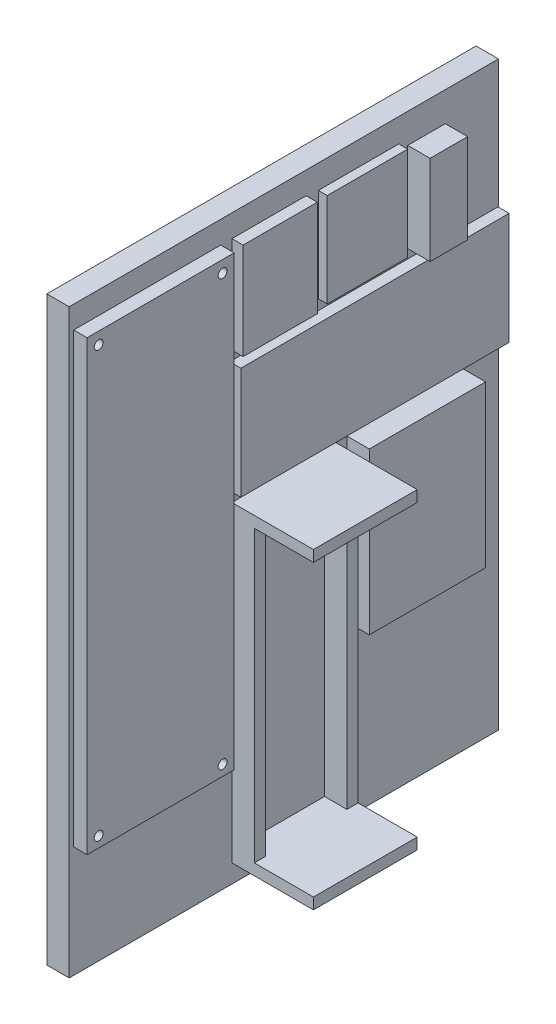
SolidWorks part; units mm, degrees
material "1060 Alloy"
ref_plane "Front Plane" through (0, 0, 0) normal (0, 0, 1) x (1, 0, 0)
ref_plane "Top Plane" through (0, 0, 0) normal (0, 1, 0) x (1, 0, 0)
ref_plane "Right Plane" through (0, 0, 0) normal (1, 0, 0) x (0, 0, -1)
sketch "Sketch1" plane through (0, 0, 0) normal (1, 0, 0) x (0, 0, -1)
  line L1 (-16.445, 50.065) -> (16.445, 50.065)
  line L2 (-16.445, 50.065) -> (-16.445, -50.065)
  line L3 (-16.445, -50.065) -> (16.445, -50.065)
  line L4 (16.445, 50.065) -> (16.445, -50.065)
  line L5 (-17.445, 55.065) -> (78.555, 55.065)
  line L6 (-17.445, 55.065) -> (-17.445, -74.935)
  line L7 (-17.445, -74.935) -> (78.555, -74.935)
  line L8 (78.555, 55.065) -> (78.555, -74.935)
  circle A0 centre (-13.855, 47.395) radius 1
  circle A4 centre (13.855, 47.395) radius 1
  circle A5 centre (13.855, -47.705) radius 1
  circle A6 centre (-13.855, -47.705) radius 1
  dimension "D3" = 2
  dimension "D4" = 2.67
  dimension "D8" = 2
  dimension "D11" = 2
  dimension "D12" = 2
  dimension "D15" = 2.36
  dimension "D1" = 32.89
  dimension "D2" = 100.13
  dimension "D5" = 2.59
  dimension "D6" = 50.065
  dimension "D7" = 16.445
  dimension "D9" = 2.59
  dimension "D10" = 2.67
  dimension "D13" = 2.59
  dimension "D14" = 2.36
  dimension "D16" = 2.59
  dimension "D17" = 95.1
  dimension "D18" = 130
  dimension "D19" = 96
  dimension "D20" = 5
  dimension "D21" = 1
extrude "Boss-Extrude1" add sketch "Sketch1" along normal blind 5 contours L4 L1 L2 L3 A6 A5 A4 A0 | L8 L5 L6 L7 L1 L4 L3 L2
sketch "Sketch3" plane through (5, 0, 0) normal (1, 0, 0) x (0, 0, -1)
  line L1 (-16.445, 50.065) -> (16.445, 50.065)
  line L2 (-16.445, 50.065) -> (-16.445, -50.065)
  line L3 (-16.445, -50.065) -> (16.445, -50.065)
  line L4 (16.445, 50.065) -> (16.445, -50.065)
  circle A0 centre (-13.855, 47.395) radius 1 construction
  circle A1 centre (13.855, 47.395) radius 1 construction
  circle A2 centre (13.855, -47.705) radius 1 construction
  circle A3 centre (-13.855, 47.395) radius 1
  circle A4 centre (13.855, 47.395) radius 1
  circle A5 centre (13.855, -47.705) radius 1
  circle A6 centre (-13.855, -47.705) radius 1
  dimension "D5" = 2
  dimension "D6" = 2.36
  dimension "D1" = 2.59
  dimension "D2" = 2.59
  dimension "D3" = 2.67
  dimension "D4" = 2.36
  dimension "D7" = 2.59
extrude "Boss-Extrude3" add sketch "Sketch3" along normal blind 3
sketch "Sketch4" plane through (5, 0, 0) normal (1, 0, 0) x (0, 0, -1)
  line L1 (18.945, 50.065) -> (35.545, 50.065)
  line L2 (18.945, 50.065) -> (18.945, 28.465)
  line L3 (18.945, 28.465) -> (35.545, 28.465)
  line L4 (35.545, 50.065) -> (35.545, 28.465)
  line L10 (16.445, -50.065) -> (16.445, 50.065) construction
  line L11 (16.445, 50.065) -> (-16.445, 50.065) construction
  point P4 (35.545, 39.265)
  point P7 (0, 50.065)
  dimension "D1" = 16.6
  dimension "D2" = 21.6
  dimension "D3" = 0
  dimension "D6" = 2.5
extrude "Boss-Extrude4" add sketch "Sketch4" along normal blind 2.5
sketch "Sketch5" plane through (5, 0, 0) normal (1, 0, 0) x (0, 0, -1)
  line L1 (18.445, 26.465) -> (78.445, 26.465)
  line L2 (18.445, 26.465) -> (18.445, 1.465)
  line L3 (18.445, 1.465) -> (78.445, 1.465)
  line L4 (78.445, 26.465) -> (78.445, 1.465)
  line L5 (18.945, 28.465) -> (35.545, 28.465) construction
  line L6 (16.445, -50.065) -> (16.445, 50.065) construction
  dimension "D1" = 60
  dimension "D2" = 25
  dimension "D3" = 2
  dimension "D4" = 2
extrude "Boss-Extrude5" add sketch "Sketch5" along normal blind 2.5
sketch "Sketch6" plane through (5, 0, 0) normal (1, 0, 0) x (0, 0, -1)
  line L1 (38.2605, 49.7462) -> (56.2605, 49.7462)
  line L2 (38.2605, 49.7462) -> (38.2605, 28.7462)
  line L3 (38.2605, 28.7462) -> (56.2605, 28.7462)
  line L4 (56.2605, 49.7462) -> (56.2605, 28.7462)
  dimension "D1" = 18
  dimension "D2" = 21
extrude "Boss-Extrude6" add sketch "Sketch6" along normal blind 2
sketch "Sketch7" plane through (5, 0, 0) normal (1, 0, 0) x (0, 0, -1)
  line L0 (56.2605, 28.7462) -> (56.2605, 49.7462) construction
  line L1 (58.2605, 48.465) -> (66.6605, 48.465)
  line L2 (58.2605, 48.465) -> (58.2605, 28.465)
  line L3 (58.2605, 28.465) -> (66.6605, 28.465)
  line L4 (66.6605, 48.465) -> (66.6605, 28.465)
  line L5 (78.445, 26.465) -> (18.445, 26.465) construction
  dimension "D1" = 8.4
  dimension "D2" = 20
  dimension "D3" = 2
  dimension "D4" = 2
extrude "Boss-Extrude7" add sketch "Sketch7" along normal blind 5
sketch "Sketch9" plane through (5, 0, 0) normal (1, 0, 0) x (0, 0, -1)
  line L0 (18.445, 1.465) -> (78.445, 1.465) construction
  line L1 (21.445, -3.535) -> (39.665, -3.535)
  line L2 (21.445, -3.535) -> (21.445, -68.335)
  line L3 (21.445, -68.335) -> (39.665, -68.335)
  line L4 (39.665, -3.535) -> (39.665, -68.335)
  line L5 (16.445, -50.065) -> (16.445, 50.065) construction
  line L7 (21.445, -3.535) -> (18.945, -3.535)
  line L8 (21.445, -3.535) -> (21.445, -68.335)
  line L9 (21.445, -68.335) -> (18.945, -68.335)
  line L10 (18.945, -3.535) -> (18.945, -68.335)
  line L11 (39.665, -3.535) -> (42.165, -3.535)
  line L12 (39.665, -3.535) -> (39.665, -68.335)
  line L13 (39.665, -68.335) -> (42.165, -68.335)
  line L14 (42.165, -3.535) -> (42.165, -68.335)
  line L15 (18.945, -68.335) -> (42.165, -68.335)
  line L19 (42.165, -3.535) -> (18.945, -3.535)
  dimension "D1" = 18.22
  dimension "D2" = 64.8
  dimension "D3" = 5
  dimension "D4" = 5
  dimension "D5" = 2.5
  dimension "D6" = 2.5
extrude "Boss-Extrude8" add sketch "Sketch9" along normal blind 5 contours L7 L10 L9 L2 | L14 L11 L4 L13
sketch "Sketch10" plane through (5, 0, 0) normal (1, 0, 0) x (0, 0, -1)
  line L1 (18.945, -68.335) -> (42.165, -68.335)
  line L2 (18.945, -68.335) -> (18.945, -70.835)
  line L3 (18.945, -70.835) -> (42.165, -70.835)
  line L4 (42.165, -68.335) -> (42.165, -70.835)
  line L5 (18.945, -3.535) -> (42.165, -3.535)
  line L6 (18.945, -3.535) -> (18.945, -1.035)
  line L7 (18.945, -1.035) -> (42.165, -1.035)
  line L8 (42.165, -3.535) -> (42.165, -1.035)
  dimension "D1" = 2.5
  dimension "D2" = 2.5
extrude "Boss-Extrude9" add sketch "Sketch10" along normal blind 18.22
sketch "Sketch11" plane through (5, 0, 0) normal (1, 0, 0) x (0, 0, -1)
  line L0 (42.165, -3.535) -> (42.165, -68.335) construction
  line L1 (44.665, -1.035) -> (70.665, -1.035)
  line L2 (44.665, -1.035) -> (44.665, -37.035)
  line L3 (44.665, -37.035) -> (70.665, -37.035)
  line L4 (70.665, -1.035) -> (70.665, -37.035)
  line L5 (18.445, 1.465) -> (78.445, 1.465) construction
  dimension "D1" = 2.5
  dimension "D2" = 2.5
  dimension "D3" = 36
  dimension "D4" = 26
sketch "Sketch12" plane through (5, 0, 0) normal (1, 0, 0) x (0, 0, -1)
  line L0 (42.165, -3.535) -> (42.165, -68.335) construction
  line L1 (44.665, -1.035) -> (70.665, -1.035)
  line L2 (44.665, -1.035) -> (44.665, -37.035)
  line L3 (44.665, -37.035) -> (70.665, -37.035)
  line L4 (70.665, -1.035) -> (70.665, -37.035)
  line L5 (18.445, 1.465) -> (78.445, 1.465) construction
  dimension "D1" = 2.5
  dimension "2.5" = 2.5
  dimension "D2" = 36
  dimension "D3" = 26
extrude "Boss-Extrude11" add sketch "Sketch12" along normal blind 5 contours L2 L1 L4 L3
extrude "Boss-Extrude10" add sketch "Sketch11" along normal blind 5
